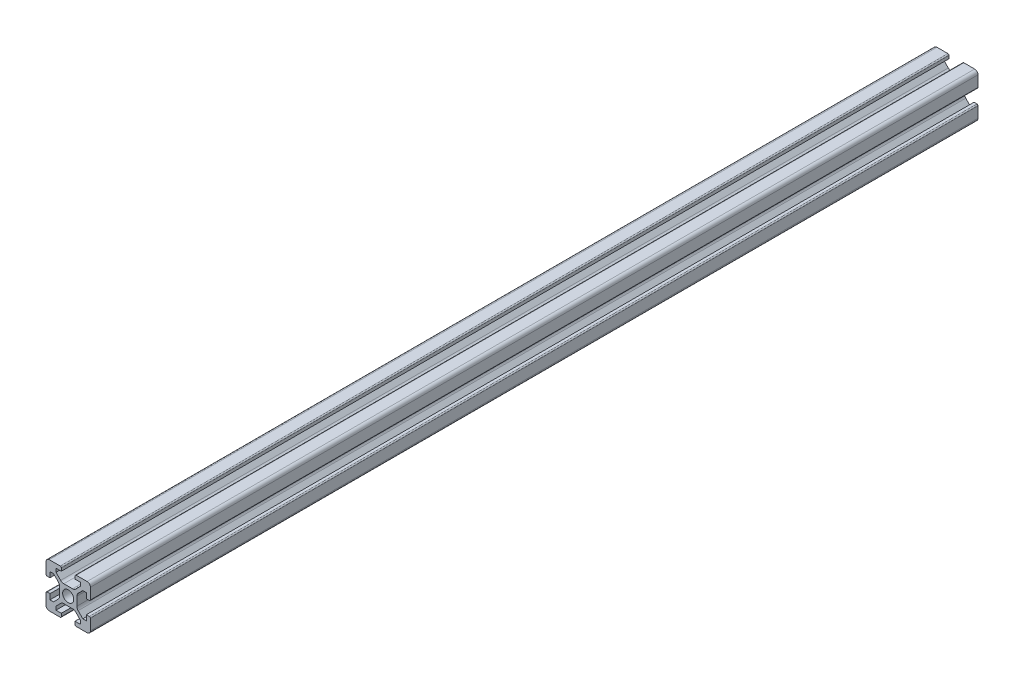
SolidWorks part; units mm, degrees
ref_plane "前视基准面" through (0, 0, 0) normal (0, 0, 1) x (1, 0, 0)
ref_plane "上视基准面" through (0, 0, 0) normal (0, 1, 0) x (1, 0, 0)
ref_plane "右视基准面" through (0, 0, 0) normal (1, 0, 0) x (0, 0, -1)
sketch "草图1" plane through (0, 0, 0) normal (0, 0, 1) x (1, 0, 0)
  line L0 (-19.2539, 0) -> (18.8323, 0) construction
  line L1 (0, 18.4429) -> (0, -19.8143) construction
  line L2 (3.9, 0) -> (3.9, 1.9716)
  line L3 (-8.5, 10) -> (-3.6, 10)
  line L4 (-10, 8.5) -> (-10, 3.6)
  line L5 (-8.5, -10) -> (-3.6, -10)
  line L6 (10, 8.5) -> (10, 3.6)
  line L7 (-10, 10) -> (10, -10) construction
  line L8 (-10, -10) -> (10, 10) construction
  line L9 (4.4858, 3.3858) -> (6.6, 5.5)
  line L10 (6.6, 5.5) -> (8.2, 5.5)
  line L11 (8.2, 5.5) -> (8.2, 3.1)
  line L12 (8.2, 3.1) -> (9.5, 3.1)
  line L17 (8.2, -3.1) -> (9.5, -3.1)
  line L18 (8.2, -5.5) -> (8.2, -3.1)
  line L19 (6.6, -5.5) -> (8.2, -5.5)
  line L20 (4.4858, -3.3858) -> (6.6, -5.5)
  line L21 (3.9, 0) -> (3.9, -1.9716)
  line L22 (10, -3.6) -> (10, -8.5)
  line L23 (-3.1, 8.2) -> (-3.1, 9.5)
  line L24 (-5.5, 8.2) -> (-3.1, 8.2)
  line L25 (-5.5, 6.6) -> (-5.5, 8.2)
  line L26 (-3.3858, 4.4858) -> (-5.5, 6.6)
  line L27 (0, 3.9) -> (-1.9716, 3.9)
  line L28 (0, 3.9) -> (1.9716, 3.9)
  line L29 (3.3858, 4.4858) -> (5.5, 6.6)
  line L30 (5.5, 6.6) -> (5.5, 8.2)
  line L31 (5.5, 8.2) -> (3.1, 8.2)
  line L32 (3.1, 8.2) -> (3.1, 9.5)
  line L33 (3.6, 10) -> (8.5, 10)
  line L34 (-8.2, -3.1) -> (-9.5, -3.1)
  line L35 (-8.2, -5.5) -> (-8.2, -3.1)
  line L36 (-6.6, -5.5) -> (-8.2, -5.5)
  line L37 (-4.4858, -3.3858) -> (-6.6, -5.5)
  line L38 (-3.9, 0) -> (-3.9, -1.9716)
  line L39 (-3.9, 0) -> (-3.9, 1.9716)
  line L40 (-4.4858, 3.3858) -> (-6.6, 5.5)
  line L41 (-6.6, 5.5) -> (-8.2, 5.5)
  line L42 (-8.2, 5.5) -> (-8.2, 3.1)
  line L43 (-8.2, 3.1) -> (-9.5, 3.1)
  line L44 (3.1, -8.2) -> (3.1, -9.5)
  line L45 (5.5, -8.2) -> (3.1, -8.2)
  line L46 (5.5, -6.6) -> (5.5, -8.2)
  line L47 (3.3858, -4.4858) -> (5.5, -6.6)
  line L48 (0, -3.9) -> (1.9716, -3.9)
  line L49 (0, -3.9) -> (-1.9716, -3.9)
  line L50 (-3.3858, -4.4858) -> (-5.5, -6.6)
  line L51 (-5.5, -6.6) -> (-5.5, -8.2)
  line L52 (-5.5, -8.2) -> (-3.1, -8.2)
  line L53 (-3.1, -8.2) -> (-3.1, -9.5)
  line L54 (3.6, -10) -> (8.5, -10)
  line L55 (-10, -3.6) -> (-10, -8.5)
  circle A0 centre (0, 0) radius 2.5
  arc A1 (3.9, 1.9716) -> (4.4858, 3.3858) centre (5.9, 1.9716) cw
  arc A2 (4.4858, -3.3858) -> (3.9, -1.9716) centre (5.9, -1.9716) cw
  arc A5 (10, 8.5) -> (8.5, 10) centre (8.5, 8.5) ccw
  arc A6 (-10, 8.5) -> (-8.5, 10) centre (-8.5, 8.5) cw
  arc A7 (-8.5, -10) -> (-10, -8.5) centre (-8.5, -8.5) cw
  arc A8 (10, -8.5) -> (8.5, -10) centre (8.5, -8.5) cw
  arc A9 (9.5, 3.1) -> (10, 3.6) centre (9.5, 3.6) ccw
  arc A10 (10, -3.6) -> (9.5, -3.1) centre (9.5, -3.6) ccw
  arc A11 (-3.6, 10) -> (-3.1, 9.5) centre (-3.6, 9.5) cw
  arc A12 (-3.3858, 4.4858) -> (-1.9716, 3.9) centre (-1.9716, 5.9) ccw
  arc A13 (1.9716, 3.9) -> (3.3858, 4.4858) centre (1.9716, 5.9) ccw
  arc A14 (3.1, 9.5) -> (3.6, 10) centre (3.6, 9.5) cw
  arc A15 (-10, -3.6) -> (-9.5, -3.1) centre (-9.5, -3.6) cw
  arc A16 (-4.4858, -3.3858) -> (-3.9, -1.9716) centre (-5.9, -1.9716) ccw
  arc A17 (-3.9, 1.9716) -> (-4.4858, 3.3858) centre (-5.9, 1.9716) ccw
  arc A18 (-9.5, 3.1) -> (-10, 3.6) centre (-9.5, 3.6) cw
  arc A19 (3.6, -10) -> (3.1, -9.5) centre (3.6, -9.5) cw
  arc A20 (3.3858, -4.4858) -> (1.9716, -3.9) centre (1.9716, -5.9) ccw
  arc A21 (-1.9716, -3.9) -> (-3.3858, -4.4858) centre (-1.9716, -5.9) ccw
  arc A22 (-3.1, -9.5) -> (-3.6, -10) centre (-3.6, -9.5) cw
  point P34 (3.9, 2.8)
  point P37 (3.9, -2.8)
  point P42 (10, 3.1)
  point P53 (10, -3.1)
  dimension "D1" = 5
  dimension "D10" = 2
  dimension "D13" = 1.5
  dimension "D8" = 0.5
  dimension "D3" = 6.1
  dimension "D4" = 11
  dimension "D5" = 6.2
  dimension "D6" = 1.8
  dimension "D7" = 3.4
  dimension "D16" = 20
extrude "凸台-拉伸1" add sketch "草图1" along normal blind 400
